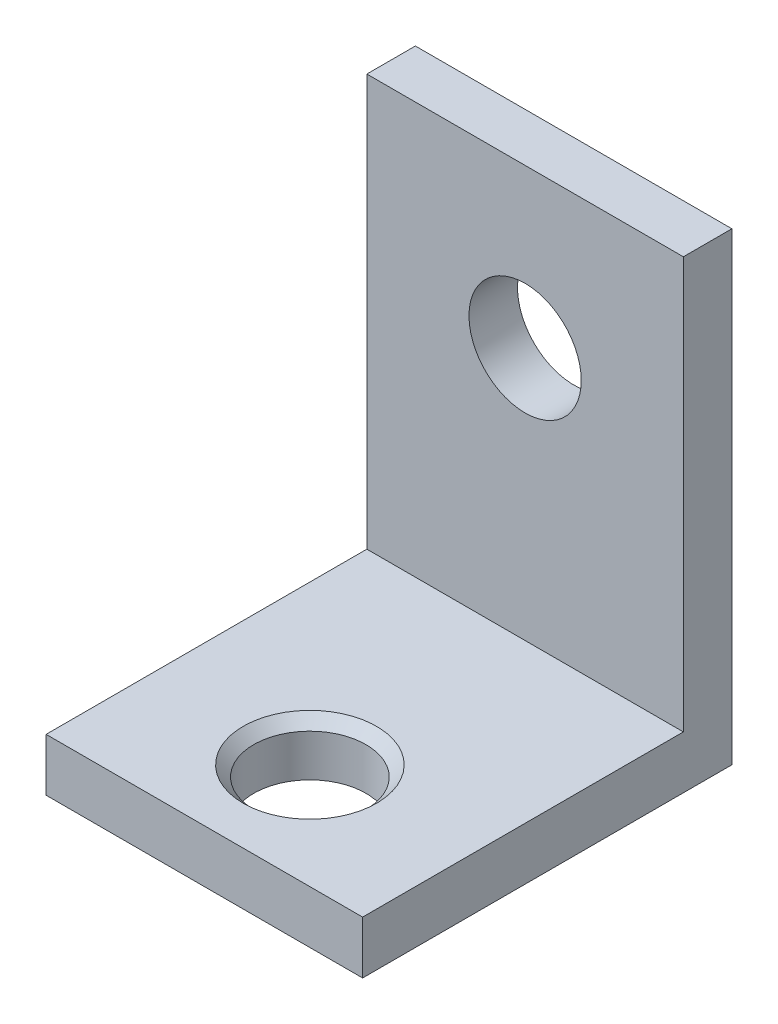
SolidWorks part; units mm, degrees
material "ABS"
ref_plane "Front Plane" through (0, 0, 0) normal (0, 0, 1) x (1, 0, 0)
ref_plane "Top Plane" through (0, 0, 0) normal (0, 1, 0) x (1, 0, 0)
ref_plane "Right Plane" through (0, 0, 0) normal (1, 0, 0) x (0, 0, -1)
sketch "Sketch1" plane through (0, 0, 0) normal (0, 1, 0) x (1, 0, 0)
  line L1 (0, 0) -> (19.05, 0)
  line L2 (0, 0) -> (0, 22.225)
  line L3 (0, 22.225) -> (19.05, 22.225)
  line L4 (19.05, 0) -> (19.05, 22.225)
  dimension "D1" = 22.225
  dimension "D2" = 19.05
extrude "Boss-Extrude1" add sketch "Sketch1" along normal blind 3.175
sketch "Sketch2" plane through (0, 3.175, 0) normal (0, 1, 0) x (1, 0, 0)
  line L0 (19.05, 0) -> (19.05, 22.225) construction
  line L1 (0, 22.225) -> (19.05, 22.225)
  line L2 (0, 22.225) -> (0, 19.05)
  line L3 (0, 19.05) -> (19.05, 19.05)
  line L4 (19.05, 22.225) -> (19.05, 19.05)
  dimension "D1" = 3.175
extrude "Boss-Extrude2" add sketch "Sketch2" along normal blind 24.765
sketch "Sketch4" plane through (0, 3.175, 0) normal (0, 1, 0) x (1, 0, 0)
  line L0 (0, 19.05) -> (0, 0) construction
  line L2 (0, 19.05) -> (19.05, 19.05) construction
  point P0 (9.525, 6.35)
  dimension "D1" = 9.525
  dimension "D2" = 12.7
sketch "Sketch6" plane through (0, 0, -19.05) normal (0, 0, 1) x (1, 0, 0)
  line L0 (0, 27.94) -> (0, 3.175) construction
  line L1 (0, 27.94) -> (19.05, 27.94) construction
  point P0 (9.525, 18.415)
  dimension "D1" = 9.525
  dimension "D2" = 9.525
hole_wizard "1/4 Clearance Hole2" positions "3DSketch2" profile "Sketch7" hole size "1/4" standard "ANSI Inch" end condition through all
sketch3d "3DSketch2"
  point P0 (9.525, 3.175, -6.35)
sketch "Sketch7" plane through (9.525, 3.175, -6.35) normal (1, 0, 0) x (0, 0, 1)
  line L0 (0, 0) -> (0, 3.175)
  line L1 (0, 3.175) -> (3.3782, 3.175)
  line L2 (3.3782, 3.175) -> (3.3782, 0.635)
  line L3 (3.3782, 0.635) -> (4.0132, 0)
  line L5 (4.0132, 0) -> (0, 0)
  line L6 (-3.3782, 0.635) -> (-4.0132, 0) construction
  line L11 (0, -6.35) -> (0, 107.95) construction
  dimension "Thru Hole Dia." = 6.7564
  dimension "Thru Hole Depth" = 3.175
  dimension "Near C'Sink Dia." = 8.0264
  dimension "Near C'Sink Angle" = 90
hole_wizard "1/4 Clearance Hole3" positions "3DSketch3" profile "Sketch8" hole size "1/4" standard "ANSI Inch" end condition through all
sketch3d "3DSketch3"
  point P0 (9.525, 18.415, -19.05)
sketch "Sketch8" plane through (9.525, 18.415, -19.05) normal (1, 0, 0) x (0, -1, 0)
  line L0 (0, 0) -> (0, 3.175)
  line L1 (0, 3.175) -> (3.3782, 3.175)
  line L2 (3.3782, 3.175) -> (3.3782, 0)
  line L5 (3.3782, 0) -> (0, 0)
  line L11 (0, -6.35) -> (0, 107.95) construction
  dimension "Thru Hole Dia." = 6.7564
  dimension "Thru Hole Depth" = 3.175
other "Move Face1" face at (12.9032, 18.415, -19.05) parameters "D1"=0.254
